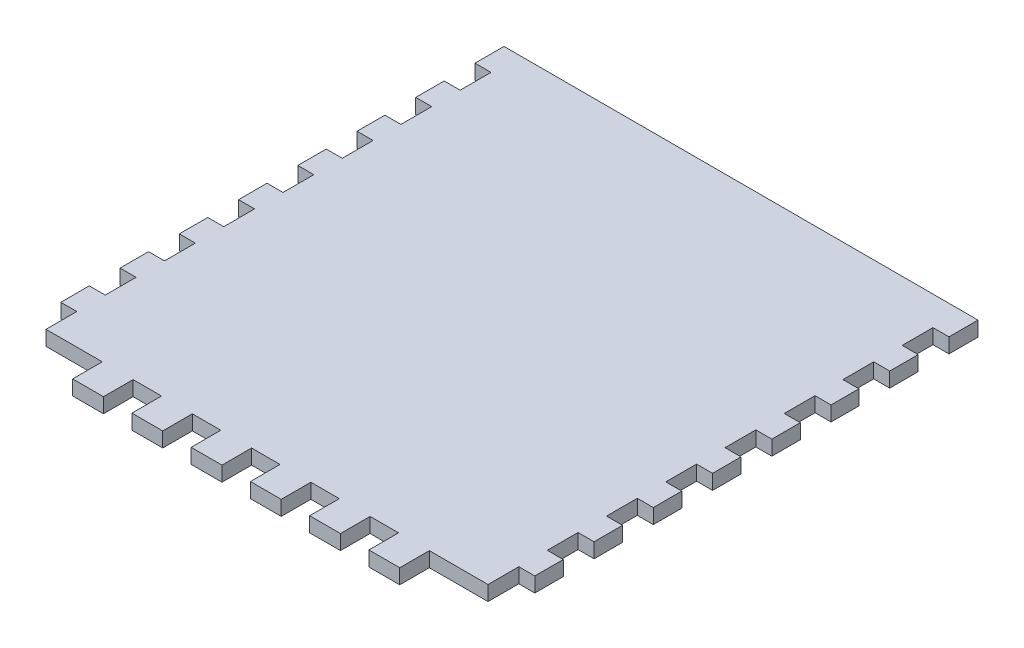
SolidWorks part; units mm, degrees
ref_plane "Front Plane" through (0, 0, 0) normal (0, 0, 1) x (1, 0, 0)
ref_plane "Top Plane" through (0, 0, 0) normal (0, 1, 0) x (1, 0, 0)
ref_plane "Right Plane" through (0, 0, 0) normal (1, 0, 0) x (0, 0, -1)
sketch "Sketch1" plane through (0, 0, 0) normal (0, 1, 0) x (1, 0, 0)
  line L1 (-50.8, -53.975) -> (50.8, -53.975)
  line L2 (-50.8, -53.975) -> (-50.8, 53.975)
  line L3 (-50.8, 53.975) -> (50.8, 53.975)
  line L4 (50.8, -53.975) -> (50.8, 53.975)
  line L5 (-50.8, -53.975) -> (50.8, 53.975) construction
  line L6 (-50.8, 53.975) -> (50.8, -53.975) construction
  line L11 (-41.275, -53.975) -> (41.275, 53.975) construction
  line L12 (-41.275, 53.975) -> (41.275, -53.975) construction
  point P0 (0, 0)
  point P5 (0, 0)
  dimension "D1" = 101.6
  dimension "D2" = 107.95
extrude "Boss-Extrude1" add sketch "Sketch1" along normal blind 3.175
sketch "Sketch2" plane through (0, 3.175, 0) normal (0, 1, 0) x (1, 0, 0)
  line L37 (22.098, -47.625) -> (28.194, -47.625)
  line L49 (28.194, -47.625) -> (28.194, -54.229)
  line L69 (0, 0) -> (0, -10.121) construction
  line L74 (-50.8, 53.975) -> (-50.8, -53.975) construction
  line L75 (-47.371, 28.448) -> (-50.8, 28.448)
  line L76 (-47.371, 28.448) -> (-47.371, 35.052)
  line L78 (-50.8, 28.448) -> (-50.8, 35.052)
  line L79 (-47.371, 22.479) -> (-50.8, 22.479)
  line L80 (-47.371, 22.479) -> (-47.371, 15.875)
  line L81 (-47.371, 15.875) -> (-50.8, 15.875)
  line L82 (-50.8, 22.479) -> (-50.8, 15.875)
  line L83 (-47.371, 9.779) -> (-50.8, 9.779)
  line L84 (-47.371, 9.779) -> (-47.371, 3.175)
  line L85 (-47.371, 3.175) -> (-50.8, 3.175)
  line L86 (-50.8, 9.779) -> (-50.8, 3.175)
  line L87 (-47.371, -2.921) -> (-50.8, -2.921)
  line L88 (-47.371, -2.921) -> (-47.371, -9.525)
  line L89 (-47.371, -9.525) -> (-50.8, -9.525)
  line L90 (-50.8, -2.921) -> (-50.8, -9.525)
  line L91 (-47.371, -15.621) -> (-50.8, -15.621)
  line L92 (-47.371, -15.621) -> (-47.371, -22.225)
  line L93 (-47.371, -22.225) -> (-50.8, -22.225)
  line L94 (-50.8, -15.621) -> (-50.8, -22.225)
  line L95 (-47.371, -28.321) -> (-50.8, -28.321)
  line L96 (-47.371, -28.321) -> (-47.371, -34.925)
  line L97 (-47.371, -34.925) -> (-50.8, -34.925)
  line L98 (-50.8, -28.321) -> (-50.8, -34.925)
  line L99 (-47.371, -41.021) -> (-50.8, -41.021)
  line L100 (-47.371, -41.021) -> (-47.371, -47.625)
  line L102 (-50.8, -41.021) -> (-50.8, -47.625)
  line L118 (50.8, -41.021) -> (50.8, -47.625)
  line L120 (47.371, -41.021) -> (47.371, -47.625)
  line L121 (47.371, -41.021) -> (50.8, -41.021)
  line L122 (50.8, -28.321) -> (50.8, -34.925)
  line L123 (47.371, -34.925) -> (50.8, -34.925)
  line L124 (47.371, -28.321) -> (47.371, -34.925)
  line L125 (47.371, -28.321) -> (50.8, -28.321)
  line L126 (50.8, -15.621) -> (50.8, -22.225)
  line L127 (47.371, -22.225) -> (50.8, -22.225)
  line L128 (47.371, -15.621) -> (47.371, -22.225)
  line L129 (47.371, -15.621) -> (50.8, -15.621)
  line L130 (50.8, -2.921) -> (50.8, -9.525)
  line L131 (47.371, -9.525) -> (50.8, -9.525)
  line L132 (47.371, -2.921) -> (47.371, -9.525)
  line L133 (47.371, -2.921) -> (50.8, -2.921)
  line L134 (50.8, 9.779) -> (50.8, 3.175)
  line L135 (47.371, 3.175) -> (50.8, 3.175)
  line L136 (47.371, 9.779) -> (47.371, 3.175)
  line L137 (47.371, 9.779) -> (50.8, 9.779)
  line L138 (50.8, 22.479) -> (50.8, 15.875)
  line L139 (47.371, 15.875) -> (50.8, 15.875)
  line L140 (47.371, 22.479) -> (47.371, 15.875)
  line L141 (47.371, 22.479) -> (50.8, 22.479)
  line L150 (-47.371, -53.721) -> (-50.8, -53.721) [skipped]
  line L151 (-47.371, -53.721) -> (-47.371, -60.325) [skipped]
  line L152 (-47.371, -60.325) -> (-50.8, -60.325) [skipped]
  line L153 (-50.8, -53.721) -> (-50.8, -60.325) [skipped]
  line L154 (-50.8, 35.052) -> (-47.371, 35.052)
  line L155 (50.8, 35.052) -> (47.371, 35.052)
  line L156 (50.8, 28.448) -> (50.8, 35.052)
  line L157 (47.371, 28.448) -> (47.371, 35.052)
  line L158 (47.371, 28.448) -> (50.8, 28.448)
  line L159 (-47.371, -47.625) -> (-35.306, -47.625)
  line L160 (-35.306, -47.625) -> (-35.306, -54.229)
  line L161 (-35.306, -54.229) -> (-28.702, -54.229)
  line L162 (-28.702, -54.229) -> (-28.702, -47.625)
  line L163 (-28.702, -47.625) -> (-22.606, -47.625)
  line L164 (-22.606, -47.625) -> (-22.606, -54.229)
  line L165 (-22.606, -54.229) -> (-16.002, -54.229)
  line L166 (-16.002, -54.229) -> (-16.002, -47.625)
  line L167 (-16.002, -47.625) -> (-9.906, -47.625)
  line L168 (-9.906, -47.625) -> (-9.906, -54.229)
  line L169 (-9.906, -54.229) -> (-3.302, -54.229)
  line L170 (-3.302, -54.229) -> (-3.302, -47.625)
  line L171 (-3.302, -47.625) -> (2.794, -47.625)
  line L172 (2.794, -47.625) -> (2.794, -54.229)
  line L173 (2.794, -54.229) -> (9.398, -54.229)
  line L174 (9.398, -54.229) -> (9.398, -47.625)
  line L175 (9.398, -47.625) -> (15.494, -47.625)
  line L176 (15.494, -47.625) -> (15.494, -54.229)
  line L177 (15.494, -54.229) -> (22.098, -54.229)
  line L178 (22.098, -54.229) -> (22.098, -47.625)
  line L180 (-50.8, -47.625) -> (-50.8, -92.545)
  line L181 (-47.371, -47.625) -> (-50.8, -47.625) [skipped]
  line L182 (-50.8, -92.545) -> (50.8, -92.545)
  line L183 (50.8, -92.545) -> (50.8, -47.625)
  line L184 (28.194, -54.229) -> (34.798, -54.229)
  line L185 (34.798, -54.229) -> (34.798, -47.625)
  line L186 (34.798, -47.625) -> (47.371, -47.625)
  line L187 (50.8, 53.975) -> (-50.8, 53.975) construction
  line L188 (50.8, 47.752) -> (47.371, 47.752)
  line L189 (50.8, 41.148) -> (50.8, 47.752)
  line L190 (47.371, 41.148) -> (47.371, 47.752)
  line L191 (47.371, 41.148) -> (50.8, 41.148)
  line L192 (-47.371, 41.148) -> (-50.8, 41.148)
  line L193 (-47.371, 41.148) -> (-47.371, 47.752)
  line L194 (-50.8, 41.148) -> (-50.8, 47.752)
  line L195 (-50.8, 47.752) -> (-47.371, 47.752)
  point P0 (-28.702, -50.927)
  dimension "D2" = 15.494
  dimension "D3" = 6.604
  dimension "D5" = 6.096
  dimension "D6" = 101.6
  dimension "D7" = 6.604
  dimension "D8" = 3.429
  dimension "D9" = 2
  dimension "D10" = 6.604
  dimension "D12" = 2
  dimension "D4" = 6.096
  dimension "D14" = 5.969
  dimension "D11" = 7
extrude "Cut-Extrude1" cut sketch "Sketch2" against normal through all both and the other way through all
